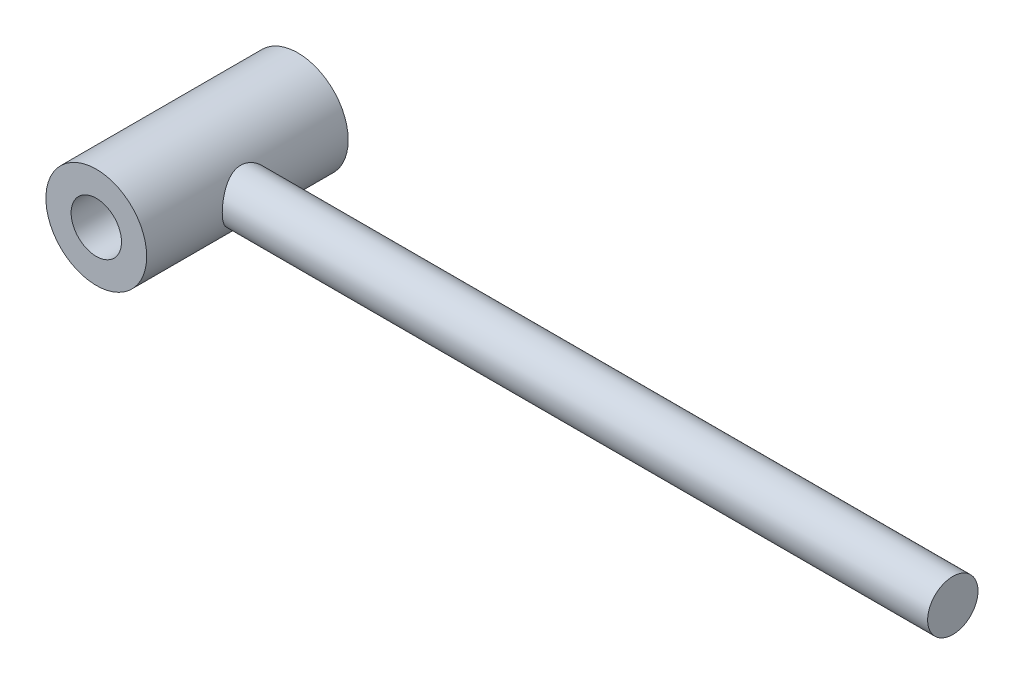
SolidWorks part; units mm, degrees
ref_plane "Plan de face" through (0, 0, 0) normal (0, 0, 1) x (1, 0, 0)
ref_plane "Plan de dessus" through (0, 0, 0) normal (0, 1, 0) x (1, 0, 0)
ref_plane "Plan de droite" through (0, 0, 0) normal (1, 0, 0) x (0, 0, -1)
sketch "Esquisse1" plane through (0, 0, 0) normal (0, 0, 1) x (1, 0, 0)
  circle A0 centre (0, 0) radius 5
  circle A1 centre (0, 0) radius 2.5
  dimension "D1" = 10
  dimension "D2" = 5
extrude "Boss.-Extru.1" add sketch "Esquisse1" along normal blind 20
ref_plane "Plan1" through (5, 0, 0) normal (1, 0, 0) x (0, 0, -1)
sketch "Esquisse2" plane through (5, 0, 0) normal (1, 0, 0) x (0, 0, -1)
  line L0 (-20, 5) -> (-20, -5) construction
  line L1 (-19.4656, 0) -> (2.9486, 0) construction
  circle A0 centre (-10, 0) radius 2.5
  dimension "D1" = 5
  dimension "D2" = 10
extrude "Boss.-Extru.2" add sketch "Esquisse2" along normal blind 70 and the other way up to next contours A0
